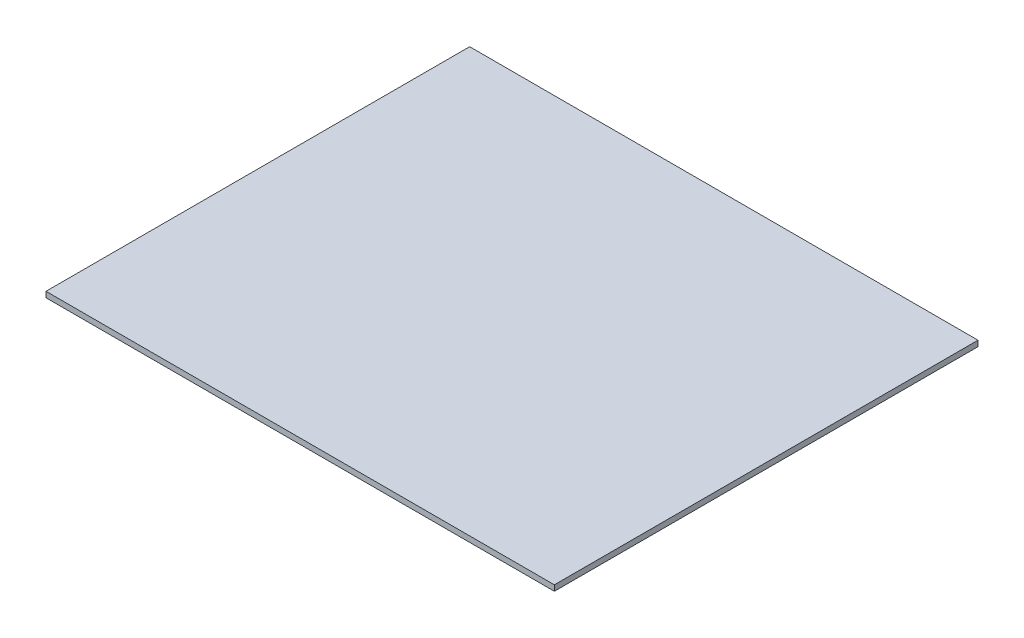
SolidWorks part; units mm, degrees
material "A-玻璃纤维"
ref_plane "前视基准面" through (0, 0, 0) normal (0, 0, 1) x (1, 0, 0)
ref_plane "上视基准面" through (0, 0, 0) normal (0, 1, 0) x (1, 0, 0)
ref_plane "右视基准面" through (0, 0, 0) normal (1, 0, 0) x (0, 0, -1)
other "Configuration Table"
sketch "草图1" plane through (0, 0, 0) normal (0, 1, 0) x (1, 0, 0)
  line L0 (0, 0) -> (360, 0)
  line L1 (360, 0) -> (360, -300)
  line L2 (360, -300) -> (0, -300)
  line L3 (0, -300) -> (0, 0)
  dimension "D1" = 360
  dimension "D2" = 300
extrude "凸台-拉伸1" add sketch "草图1" along normal blind 4
